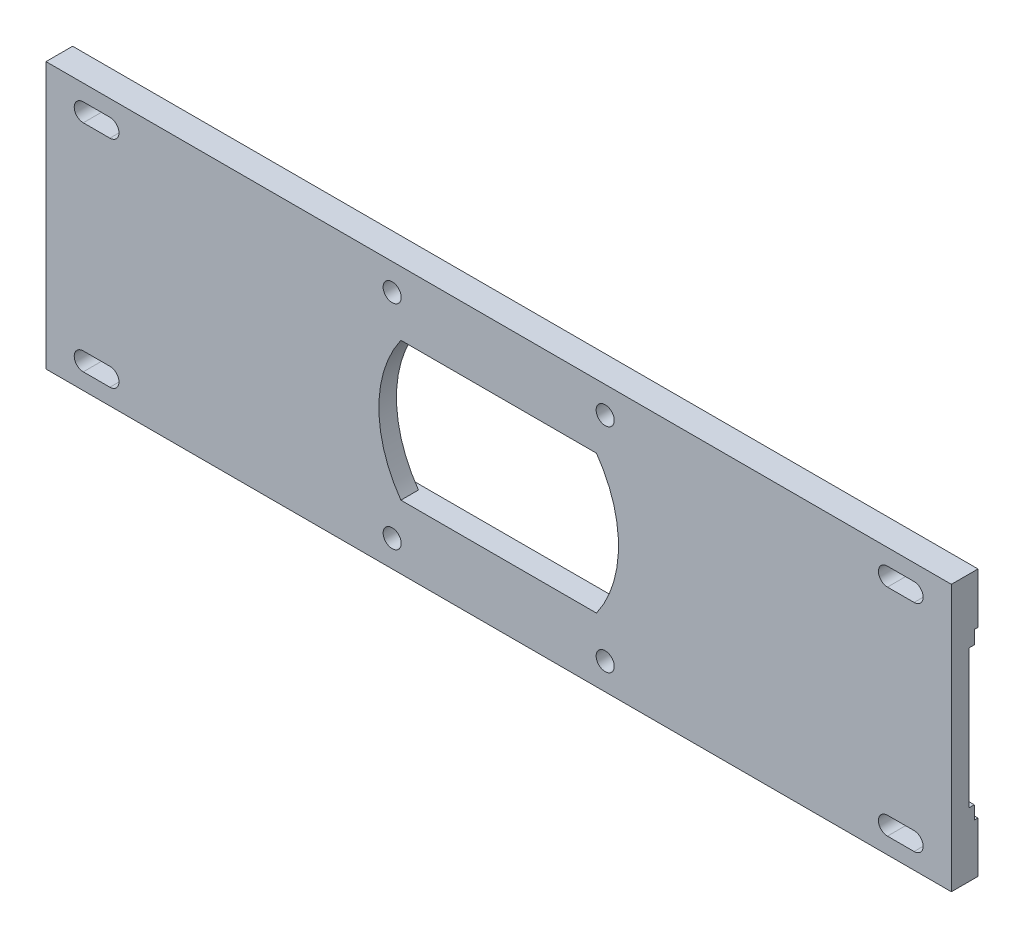
SolidWorks part; units mm, degrees
ref_plane "Płaszczyzna przednia" through (0, 0, 0) normal (0, 0, 1) x (1, 0, 0)
ref_plane "Płaszczyzna górna" through (0, 0, 0) normal (0, 1, 0) x (1, 0, 0)
ref_plane "Płaszczyzna prawa" through (0, 0, 0) normal (1, 0, 0) x (0, 0, -1)
sketch "Szkic1" plane through (0, 0, 0) normal (0, 0, 1) x (1, 0, 0)
  line L1 (-73.3595, 22.802) -> (96.6405, 22.802)
  line L2 (-73.3595, 22.802) -> (-73.3595, -27.198)
  line L3 (-73.3595, -27.198) -> (96.6405, -27.198)
  line L4 (96.6405, 22.802) -> (96.6405, -27.198)
  dimension "D1" = 170
  dimension "D2" = 50
extrude "Dodanie-wyciągnięcie1" add sketch "Szkic1" along normal blind 5
sketch "Szkic2" plane through (-73.3595, 0, 0) normal (-1, 0, 0) x (0, 0, 1)
  line L0 (5, -27.198) -> (0, -27.198) construction
  line L3 (0, -17.698) -> (0.7, -17.698)
  line L4 (0, -17.698) -> (0, 13.302)
  line L5 (0, 13.302) -> (0.7, 13.302)
  line L6 (0.7, -17.698) -> (0.7, 13.302)
  line L7 (5, 22.802) -> (0, 22.802) construction
  dimension "D1" = 0.7
  dimension "D2" = 9.5
  dimension "D3" = 9.5
  dimension "D4" = 31
extrude "Wytnij-wyciągnięcie1" cut sketch "Szkic2" against normal through all
sketch "Szkic3" plane through (-73.3595, 0, 0) normal (-1, 0, 0) x (0, 0, 1)
  line L0 (0.7, -2.198) -> (5, -2.198) construction
  line L1 (0.7, -17.698) -> (0.7, 13.302) construction
  line L2 (5, 22.802) -> (5, -27.198) construction
  line L6 (0.7, -15.198) -> (1.7, -15.198)
  line L7 (0.7, -15.198) -> (0.7, 10.802)
  line L8 (0.7, 10.802) -> (1.7, 10.802)
  line L9 (1.7, -15.198) -> (1.7, 10.802)
  circle A0 centre (0.7, -2.198) radius 13 construction
  dimension "D1" = 1
  dimension "D2" = 26
extrude "Wytnij-wyciągnięcie2" cut sketch "Szkic3" against normal through all
ref_plane "Płaszczyzna1" through (-73.3595, 10.802, 1.7) normal (0, 0, -1) x (-1, 0, 0)
sketch "Szkic4" plane through (0, 0, 5) normal (0, 0, 1) x (1, 0, 0)
  circle A0 centre (-8.3595, -22.198) radius 1.7
  circle A1 centre (31.6405, -22.198) radius 1.7
  circle A2 centre (31.6405, 17.802) radius 1.7
  circle A3 centre (-8.3595, 17.802) radius 1.7
extrude "Wytnij-wyciągnięcie3" cut sketch "Szkic4" against normal through all
sketch "Szkic5" plane through (0, 0, 5) normal (0, 0, 1) x (1, 0, 0)
  line L0 (-8.3595, -22.198) -> (31.6405, 17.802) construction
  line L1 (-8.3595, 17.802) -> (31.6405, -22.198) construction
  circle A0 centre (11.6405, -2.198) radius 22.5
  dimension "D1" = 45
extrude "Wytnij-wyciągnięcie4" cut sketch "Szkic5" against normal blind 10
sketch "Szkic6" plane through (0, 0, 0) normal (0, 0, -1) x (-1, 0, 0)
  line L0 (59.6595, 18.052) -> (57.9782, 18.052) construction
  line L2 (73.3595, 22.802) -> (73.3595, 13.302) construction
  line L3 (59.6595, 18.052) -> (73.3595, 18.052) construction
  line L5 (66.3595, 19.752) -> (61.3595, 19.752)
  line L7 (61.3595, 16.352) -> (66.3595, 16.352)
  arc A5 (61.3595, 19.752) -> (61.3595, 16.352) centre (61.3595, 18.052) ccw
  arc A7 (66.3595, 16.352) -> (66.3595, 19.752) centre (66.3595, 18.052) ccw
  dimension "D1" = 5
  dimension "D2" = 7
extrude "Wytnij-wyciągnięcie5" cut sketch "Szkic6" against normal through all
ref_plane "Płaszczyzna3" through (0, -2.198, 0) normal (0, -1, 0) x (-1, 0, 0)
mirror "Lustro1" about plane through (0, -2.198, 0) normal (0, -1, 0) of "Wytnij-wyciągnięcie5"
ref_plane "Płaszczyzna4" through (11.6405, 0, 0) normal (1, 0, 0) x (0, 0, -1)
mirror "Lustro2" about plane through (11.6405, 0, 0) normal (1, 0, 0) of "Lustro1", "Wytnij-wyciągnięcie5"
sketch "Szkic7" plane through (0, 0, 0) normal (0, 0, -1) x (-1, 0, 0)
  line L0 (-96.6405, 22.802) -> (73.3595, 22.802) construction
  line L1 (-27.95, 13.302) -> (4.8824, 13.302)
  line L2 (-27.95, 13.302) -> (-27.95, 22.802)
  line L3 (-27.95, 22.802) -> (4.8824, 22.802)
  line L4 (4.8824, 13.302) -> (4.8824, 22.802)
extrude "Dodanie-wyciągnięcie2" add sketch "Szkic7" against normal through all
sketch "Szkic8" plane through (0, 0, 0) normal (0, 0, -1) x (-1, 0, 0)
  line L0 (73.3595, -27.198) -> (-96.6405, -27.198) construction
  line L1 (-27.95, -17.698) -> (6.2865, -17.698)
  line L2 (-27.95, -17.698) -> (-27.95, -27.198)
  line L3 (-27.95, -27.198) -> (6.2865, -27.198)
  line L4 (6.2865, -17.698) -> (6.2865, -27.198)
extrude "Dodanie-wyciągnięcie3" add sketch "Szkic8" against normal through all
sketch "Szkic9" plane through (0, 0, 0.7) normal (0, 0, -1) x (-1, 0, 0)
  line L0 (4.669, 13.302) -> (73.3595, 13.302) construction
  line L1 (-30.0048, 10.802) -> (9.4595, 10.802)
  line L2 (-30.0048, 10.802) -> (-30.0048, 13.302)
  line L3 (-30.0048, 13.302) -> (9.4595, 13.302)
  line L4 (9.4595, 10.802) -> (9.4595, 13.302)
extrude "Dodanie-wyciągnięcie4" add sketch "Szkic9" against normal through all
sketch "Szkic10" plane through (0, 0, 0.7) normal (0, 0, -1) x (-1, 0, 0)
  line L0 (4.669, -17.698) -> (73.3595, -17.698) construction
  line L1 (-30.0048, -15.198) -> (9.5081, -15.198)
  line L2 (-30.0048, -15.198) -> (-30.0048, -17.698)
  line L3 (-30.0048, -17.698) -> (9.5081, -17.698)
  line L4 (9.5081, -15.198) -> (9.5081, -17.698)
extrude "Dodanie-wyciągnięcie5" add sketch "Szkic10" against normal through all
